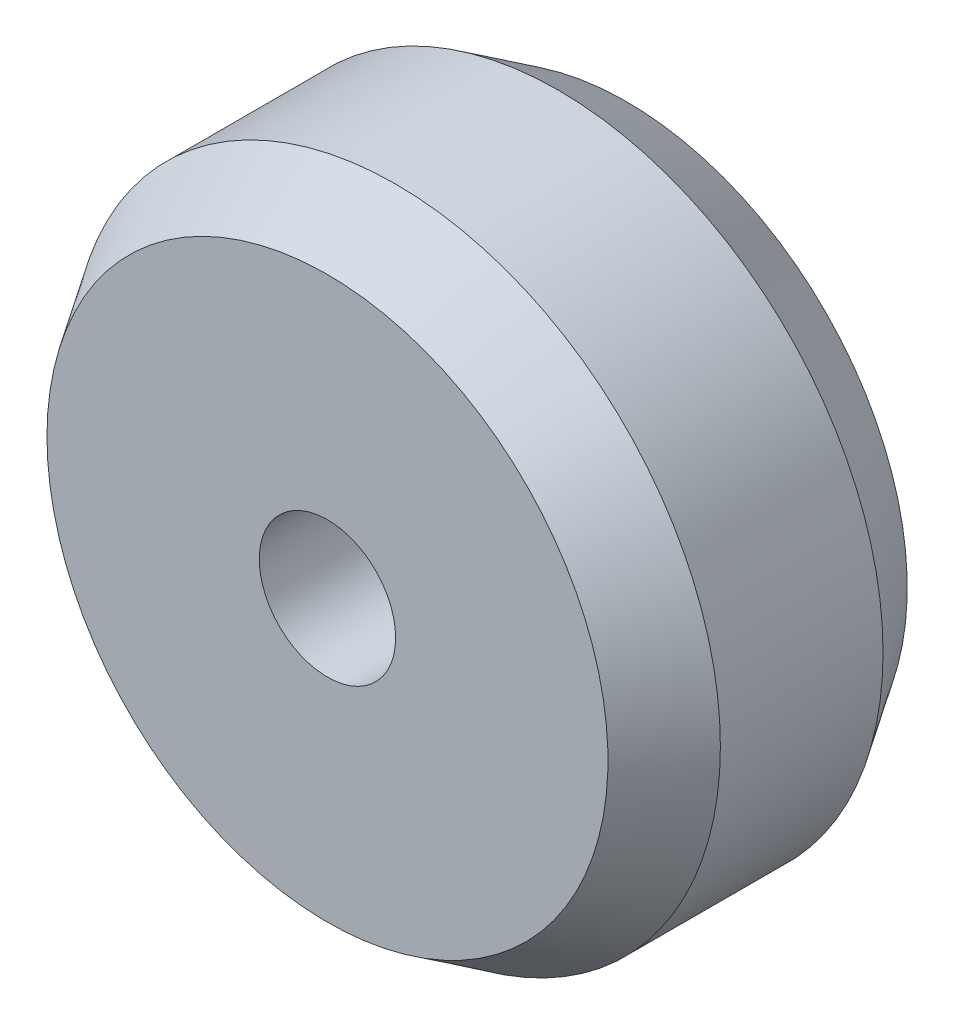
SolidWorks part; units mm, degrees
ref_plane "Front Plane" through (0, 0, 0) normal (0, 0, 1) x (1, 0, 0)
ref_plane "Top Plane" through (0, 0, 0) normal (0, 1, 0) x (1, 0, 0)
ref_plane "Right Plane" through (0, 0, 0) normal (1, 0, 0) x (0, 0, -1)
sketch "Sketch1" plane through (0, 0, 0) normal (0, 0, 1) x (1, 0, 0)
  circle A0 centre (0, 0) radius 11.975
  dimension "D1" = 23.95
extrude "Boss-Extrude1" add sketch "Sketch1" along normal blind 11.04
sketch "Sketch2" plane through (0, 0, 0) normal (0, 0, 1) x (1, 0, 0)
  circle A0 centre (0, 0) radius 2.515
  dimension "D1" = 5.03
extrude "Cut-Extrude1" cut sketch "Sketch2" along normal blind 11.04
sketch "Sketch3" plane through (0, 0, 0) normal (0, 1, 0) x (1, 0, 0)
  line L0 (-7.2922, 0) -> (-10.3472, 0)
  line L1 (-13.1725, 0) -> (13.1725, 0) construction
  line L2 (-10.3472, 0) -> (-11.975, -2.52)
  line L3 (-11.975, -2.52) -> (-11.975, -8.52)
  line L4 (-11.975, -8.52) -> (-10.3472, -11.04)
  line L6 (-11.975, -11.04) -> (11.975, -11.04) construction
  line L7 (-10.3472, -11.04) -> (-6.4583, -11.04)
  line L10 (-11.975, 0) -> (-11.975, -11.04) construction
  line L11 (-11.975, 0) -> (-11.975, -11.04) construction
  line L12 (-7.2922, 0) -> (-13.1683, 5.3701)
  line L13 (-13.1683, 5.3701) -> (-21.8941, -6.3402)
  line L14 (-21.8941, -6.3402) -> (-5.81, -18.325)
  line L15 (-5.81, -18.325) -> (-6.4583, -11.04)
  line L16 (0, 5.8546) -> (0, -19.7446) construction
  point P4 (-11.975, -5.52)
  point P17 (-11.975, -5.52)
  dimension "D1" = 6
  dimension "D2" = 3
revolve "Cut-Revolve4" cut sketch "Sketch3" angle 360 about L16
ref_plane "Plane1" through (0, 0, 5.52) normal (0, 0, 1) x (1, 0, 0)
